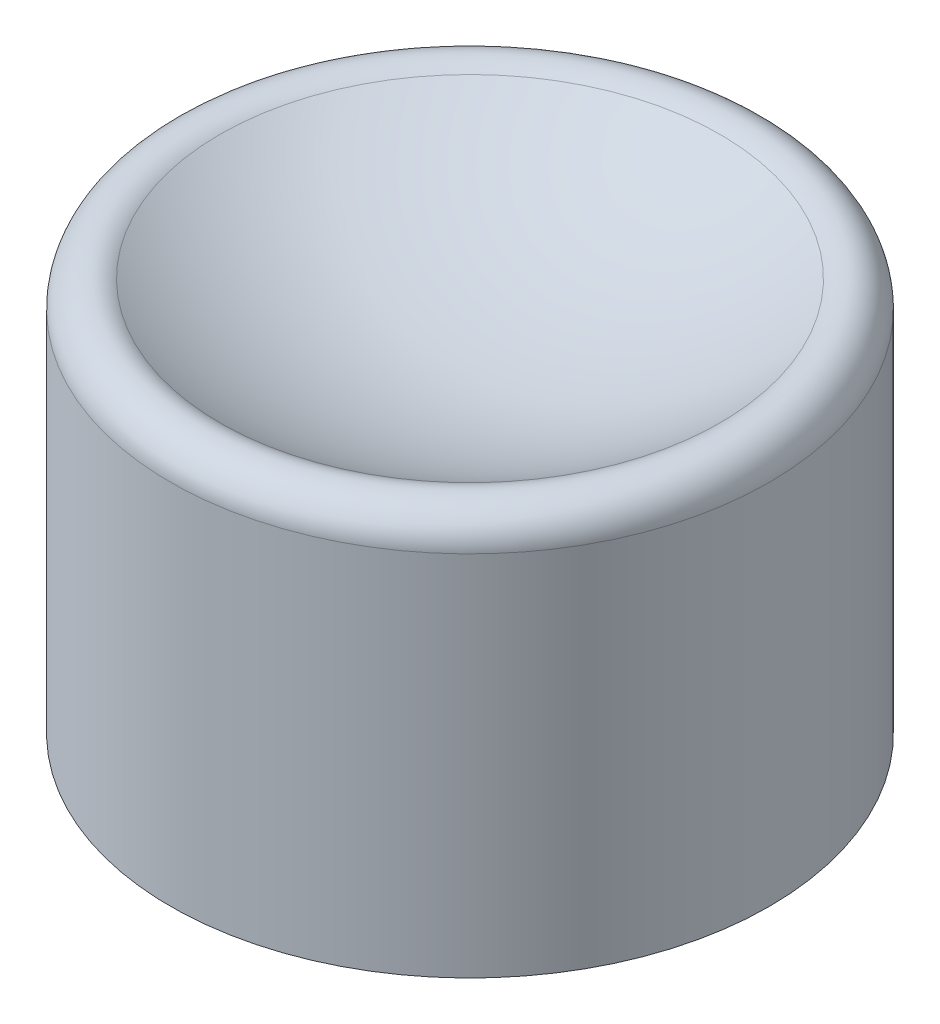
SolidWorks part; units mm, degrees
ref_plane "Front Plane" through (0, 0, 0) normal (0, 0, 1) x (1, 0, 0)
ref_plane "Top Plane" through (0, 0, 0) normal (0, 1, 0) x (1, 0, 0)
ref_plane "Right Plane" through (0, 0, 0) normal (1, 0, 0) x (0, 0, -1)
sketch "Sketch1" plane through (0, 0, 0) normal (0, 0, 1) x (1, 0, 0)
  line L0 (0, 0) -> (0, -66.4851) construction
  line L1 (55, 0) -> (-55, 0) construction
  line L2 (-1.5494, 0) -> (-1.5494, 3.048)
  line L3 (-1.5494, 3.048) -> (-0.762, 3.048)
  line L4 (-0.762, 3.048) -> (-0.762, 4.064)
  line L5 (-0.762, 4.064) -> (0, 4.064)
  line L6 (0, -55) -> (0, 55) construction
  line L7 (0, 4.064) -> (0, 5.08)
  line L8 (-4.7625, 5.842) -> (-4.7625, 0)
  line L9 (-4.7625, 0) -> (-3.4925, 0)
  line L10 (-3.4925, 0) -> (-3.4925, 4.064)
  line L11 (-3.4925, 4.064) -> (-2.0574, 4.064)
  line L12 (-2.0574, 4.064) -> (-2.0574, 0)
  line L13 (-2.0574, 0) -> (-1.5494, 0)
  line L14 (0, 5.08) -> (3.3062, 5.08) construction
  arc A0 (-4.7625, 5.842) -> (-3.976, 6.2669) centre (-4.2545, 5.842) cw
  arc A1 (-3.976, 6.2669) -> (0, 5.08) centre (0, 12.3333) ccw
  dimension "D4" = 1.524
  dimension "D5" = 6.35
  dimension "D9" = 0.508
  dimension "D1" = 9.525
  dimension "D2" = 3.0988
  dimension "D3" = 3.048
  dimension "D6" = 0.508
  dimension "D7" = 1.016
  dimension "D8" = 1.27
  dimension "D10" = 5.08
revolve "Revolve1" add sketch "Sketch1" angle 360 about L0
